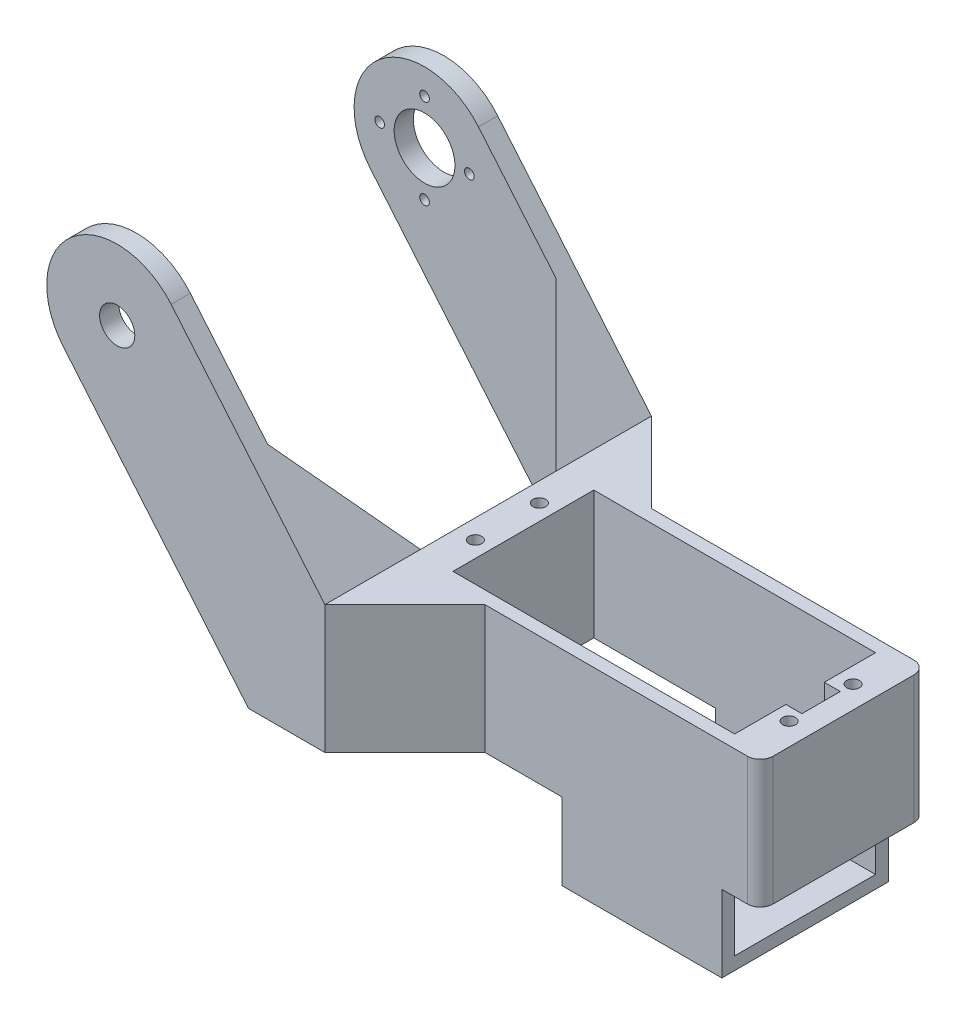
SolidWorks part; units mm, degrees
ref_plane "Alzado" through (0, 0, 0) normal (0, 0, 1) x (1, 0, 0)
ref_plane "Planta" through (0, 0, 0) normal (0, 1, 0) x (1, 0, 0)
ref_plane "Vista lateral" through (0, 0, 0) normal (1, 0, 0) x (0, 0, -1)
sketch "Croquis2" plane through (0, 0, 0) normal (0, 1, 0) x (1, 0, 0)
  line L0 (-30, 13) -> (-30, -13)
  line L1 (-22, 11) -> (22, 11)
  line L2 (-22, 11) -> (-22, -11)
  line L3 (-22, -11) -> (22, -11)
  line L4 (22, 11) -> (22, -11)
  line L5 (-22, 11) -> (22, -11) construction
  line L6 (-22, -11) -> (22, 11) construction
  line L7 (-30, -13) -> (28, -13)
  line L8 (28, 13) -> (28, -13)
  line L9 (-30, 13) -> (28, 13)
  point P0 (0, 0)
  point P10 (28, 0)
  point P11 (22, 0)
  dimension "D1" = 44
  dimension "D2" = 22
  dimension "D3" = 8
  dimension "D4" = 6
  dimension "D5" = 26
extrude "Saliente-Extruir3" add sketch "Croquis2" along normal blind 20
sketch "Croquis4" plane through (0, 20, 0) normal (0, 1, 0) x (1, 0, 0)
  line L14 (22, -11) -> (22, 11) construction
  line L15 (-22, 11) -> (-22, -11) construction
  line L16 (22, 3) -> (22, -3)
  line L17 (22, -3) -> (24.5, -3)
  line L18 (24.5, -3) -> (24.5, 3)
  line L19 (24.5, 3) -> (22, 3)
  circle A4 centre (-24.5, 5) radius 1
  circle A5 centre (-24.5, -5) radius 1
  circle A6 centre (24.5, -5) radius 1
  circle A7 centre (24.5, 5) radius 1
  point P9 (-22, 0)
  point P12 (22, 0)
  dimension "D2" = 2.5
  dimension "D1" = 2
  dimension "D3" = 10
  dimension "D4" = 2.5
  dimension "D5" = 5
  dimension "D6" = 6
  dimension "D7" = 2.5
extrude "Cut-Extrude1" cut sketch "Croquis4" against normal through all
sketch "Sketch1" plane through (-30, 0, 0) normal (-1, 0, 0) x (0, 0, 1)
  line L1 (25.5, 0) -> (-25.5, 0)
  line L2 (25.5, 0) -> (25.5, 20)
  line L3 (25.5, 20) -> (-25.5, 20)
  line L4 (-25.5, 0) -> (-25.5, 20)
  point P4 (0, 0)
  dimension "D1" = 51
extrude "Boss-Extrude1" add sketch "Sketch1" against normal blind 2.5
sketch "Croquis6" plane through (0, 0, 25.5) normal (0, 0, 1) x (1, 0, 0)
  line L0 (-27.5, 0) -> (-39.437, 0)
  line L1 (-39.437, 0) -> (-68.3624, 34.472)
  line L3 (-27.5, 20) -> (-51.5094, 48.6133)
  circle A0 centre (-59.9359, 41.5427) radius 2.75
  arc A1 (-68.3624, 34.472) -> (-51.5094, 48.6133) centre (-59.9359, 41.5427) cw
  point P20 (-59.9359, 41.5427)
  dimension "D1" = 5.5
  dimension "D6" = 22
  dimension "D7" = 45
  dimension "D5" = 130
extrude "Saliente-Extruir5" add sketch "Croquis6" against normal blind 3
sketch "Sketch3" plane through (0, 0, -25.5) normal (0, 0, -1) x (-1, 0, 0)
  line L11 (51.5094, 48.6133) -> (27.5, 20)
  line L12 (27.5, 20) -> (30, 20)
  line L13 (30, 20) -> (30, 0)
  line L14 (30, 0) -> (39.437, 0)
  line L15 (39.437, 0) -> (68.3624, 34.472)
  line L16 (51.5094, 48.6133) -> (27.5, 20)
  line L17 (27.5, 20) -> (30, 20)
  line L18 (30, 20) -> (30, 0)
  line L19 (30, 0) -> (39.437, 0)
  line L20 (39.437, 0) -> (68.3624, 34.472)
  arc A4 (68.3624, 34.472) -> (51.5094, 48.6133) centre (59.9359, 41.5427) ccw
  arc A9 (68.3624, 34.472) -> (51.5094, 48.6133) centre (59.9359, 41.5427) ccw
  circle A14 centre (66.9359, 41.5427) radius 0.75
  circle A15 centre (59.9359, 34.5427) radius 0.75
  circle A16 centre (59.9359, 48.5427) radius 0.75
  circle A17 centre (52.9359, 41.5427) radius 0.75
  circle A19 centre (59.9359, 41.5427) radius 4.75
  dimension "D2" = 9.5
  dimension "D1" = 0
extrude "Boss-Extrude2" add sketch "Sketch3" against normal blind 3
sketch "Sketch5" plane through (22, 0, 0) normal (1, 0, 0) x (0, 0, -1)
  line L0 (-13, 0) -> (-13, -12)
  line L1 (-13, -12) -> (13, -12)
  line L2 (13, -12) -> (13, 0)
  line L3 (-11, 0) -> (-11, -10)
  line L4 (-11, -10) -> (11, -10)
  line L5 (11, -10) -> (11, 0)
  line L6 (-13, 0) -> (-11, 0)
  line L7 (13, 0) -> (11, 0)
  line L8 (-13, 0) -> (13, 0) construction
  dimension "D2" = 10
  dimension "D1" = 2
extrude "Boss-Extrude3" add sketch "Sketch5" against normal blind 25
fillet "Fillet1" radius 2 2 edges at (28, 10, -13) (28, 10, 13)
sketch "Sketch6" plane through (0, -12, 0) normal (0, -1, 0) x (1, 0, 0)
  circle A0 centre (10, 0) radius 2.15
  dimension "D3" = 4.3
extrude "Boss-Extrude4" add sketch "Sketch6" along normal blind 5
fillet "Fillet4" radius 1 1 edges at (10, -12, -2.15)
sketch "Sketch8" plane through (0, 20, 0) normal (0, 1, 0) x (1, 0, 0)
  line L0 (-27.5, 25.5) -> (-27.5, 13)
  line L1 (-27.5, 13) -> (-15, 13)
  line L2 (26, 13) -> (-27.5, 13) construction
  line L3 (-15, 13) -> (-27.5, 25.5)
  line L4 (-28.8985, 0) -> (28.8985, 0) construction
  line L5 (-27.5, -13) -> (-15, -13)
  line L6 (-27.5, -25.5) -> (-27.5, -13)
  line L7 (-15, -13) -> (-27.5, -25.5)
  dimension "D1" = 45
extrude "Boss-Extrude5" add sketch "Sketch8" against normal up to surface (20 mm away) up to face at (24.5, 0, -6)
sketch "Sketch9" plane through (0, 0, 0) normal (0, -1, 0) x (1, 0, 0)
  line L0 (-39.437, 22.5) -> (-26.5, 9.563)
  line L2 (-26.5, 9.563) -> (-26.5, 22.5)
  line L3 (-26.5, 22.5) -> (-39.437, 22.5)
  line L4 (-27.5, 22.5) -> (-51.5094, 22.5) construction
  line L5 (-27.5, 22.5) -> (-30, 22.5) construction
  line L6 (28.8985, 0) -> (-28.8985, 0) construction
  line L7 (-26.5, -9.563) -> (-26.5, -22.5)
  line L8 (-39.437, -22.5) -> (-26.5, -9.563)
  line L9 (-26.5, -22.5) -> (-39.437, -22.5)
  dimension "D1" = 45
extrude "Boss-Extrude6" add sketch "Sketch9" against normal up to surface (18.8082 mm away)
sketch "Sketch10" plane through (0, 20, 0) normal (0, 1, 0) x (1, 0, 0)
  line L0 (-30, 13.063) -> (-30, -13.063)
  line L1 (-30, -13.063) -> (-27.5, -10.563)
  line L2 (-30, 13.063) -> (-27.5, 10.563)
  line L3 (-27.5, 10.563) -> (-27.5, -10.563)
extrude "Cut-Extrude2" cut sketch "Sketch10" against normal through all
